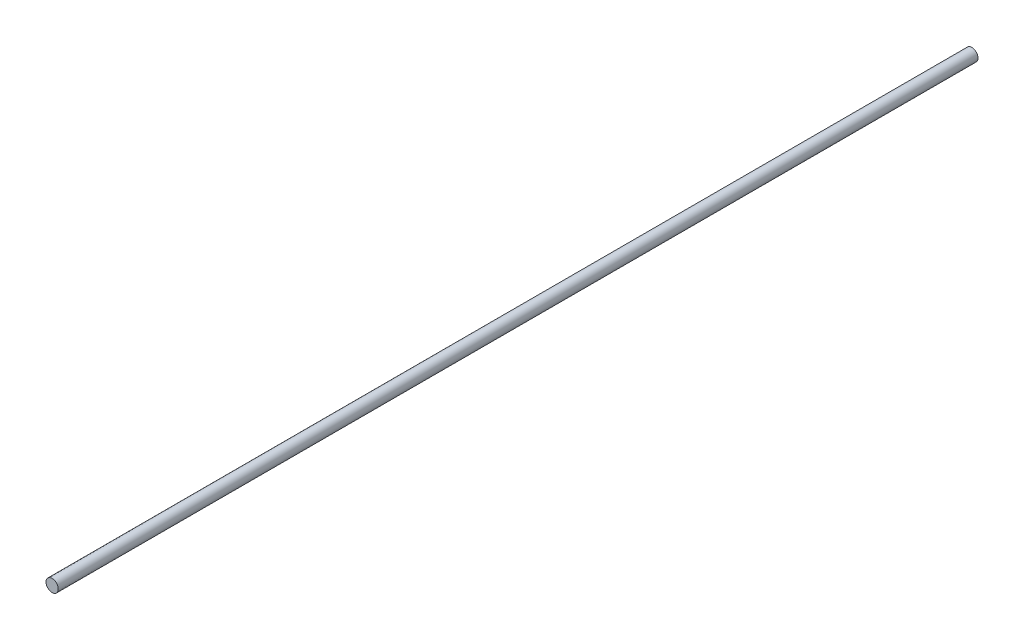
SolidWorks part; units mm, degrees
ref_plane "前视基准面" through (0, 0, 0) normal (0, 0, 1) x (1, 0, 0)
ref_plane "上视基准面" through (0, 0, 0) normal (0, 1, 0) x (1, 0, 0)
ref_plane "右视基准面" through (0, 0, 0) normal (1, 0, 0) x (0, 0, -1)
other "Configuration Table"
sketch "草图1" plane through (0, 0, 0) normal (0, 0, 1) x (1, 0, 0)
  circle A0 centre (0, 0) radius 4
  dimension "D1" = 8
extrude "凸台-拉伸1" add sketch "草图1" along normal blind 600
